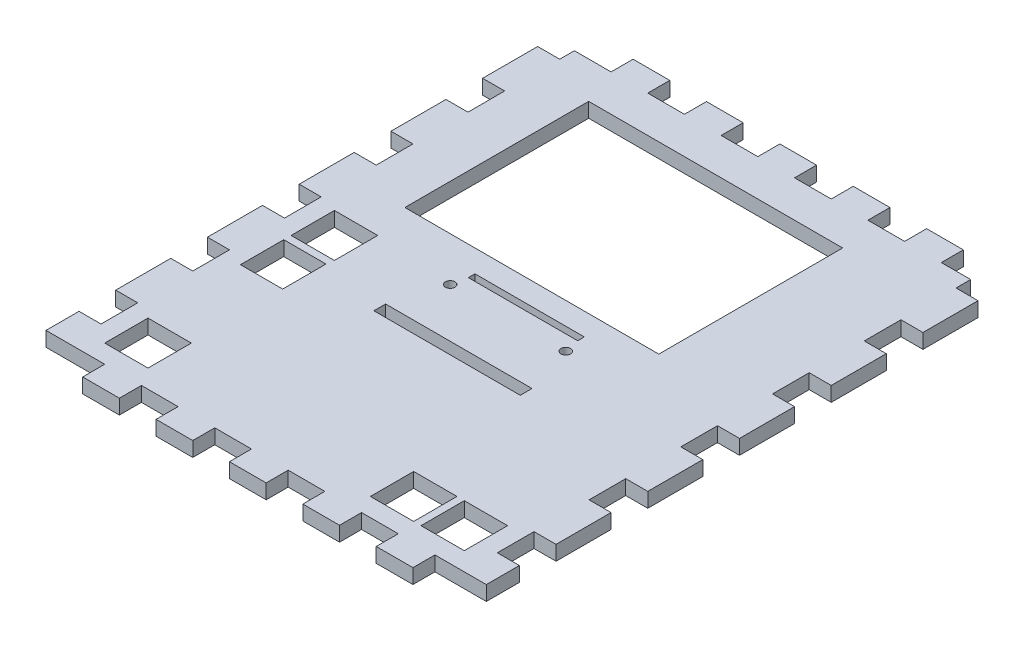
SolidWorks part; units mm, degrees
ref_plane "Спереди" through (0, 0, 0) normal (0, 0, 1) x (1, 0, 0)
ref_plane "Сверху" through (0, 0, 0) normal (0, 1, 0) x (1, 0, 0)
ref_plane "Справа" through (0, 0, 0) normal (1, 0, 0) x (0, 0, -1)
other "Configuration Table"
sketch "Эскиз1" plane through (0, 0, 0) normal (0, 1, 0) x (1, 0, 0)
  line L1 (0, 0) -> (108, 0)
  line L2 (0, 0) -> (0, -138)
  line L3 (0, -138) -> (108, -138)
  line L4 (108, 0) -> (108, -138)
  dimension "D1" = 138
  dimension "D2" = 108
extrude "Бобышка-Вытянуть1" add sketch "Эскиз1" along normal blind 4
sketch "Эскиз2" plane through (0, 4, 0) normal (0, 1, 0) x (1, 0, 0)
  line L0 (0, 0) -> (0, -138) construction
  line L1 (13.9, -10) -> (83.11, -10)
  line L2 (13.9, -10) -> (13.9, -60.1)
  line L3 (13.9, -60.1) -> (83.11, -60.1)
  line L4 (83.11, -10) -> (83.11, -60.1)
  line L6 (108, 0) -> (0, 0) construction
  dimension "D1" = 50.1
  dimension "D2" = 69.21
  dimension "D3" = 13.9
  dimension "D4" = 10
extrude "Вырез-Вытянуть1" cut sketch "Эскиз2" against normal through all
sketch "Эскиз4" plane through (0, 0, 0) normal (-1, 0, 0) x (0, 0, 1)
  line L0 (0, 4) -> (138, 4) construction
  line L1 (4, 4) -> (19, 4)
  line L2 (4, 4) -> (4, 0)
  line L3 (4, 0) -> (19, 0)
  line L4 (19, 4) -> (19, 0)
  line L5 (0, 0) -> (138, 0) construction
  line L6 (0, 4) -> (0, 0) construction
  line L7 (29, 4) -> (29, 0)
  line L8 (29, 4) -> (44, 4)
  line L9 (44, 4) -> (44, 0)
  line L10 (29, 0) -> (44, 0)
  line L11 (54, 4) -> (54, 0)
  line L12 (54, 4) -> (69, 4)
  line L13 (69, 4) -> (69, 0)
  line L14 (54, 0) -> (69, 0)
  line L15 (79, 4) -> (79, 0)
  line L16 (79, 4) -> (94, 4)
  line L17 (94, 4) -> (94, 0)
  line L18 (79, 0) -> (94, 0)
  line L19 (104, 4) -> (104, 0)
  line L20 (104, 4) -> (119, 4)
  line L21 (119, 4) -> (119, 0)
  line L22 (104, 0) -> (119, 0)
  dimension "D1" = 15
  dimension "D2" = 4
  dimension "D3" = 5
extrude "Бобышка-Вытянуть2" add sketch "Эскиз4" along normal blind 6
sketch "Эскиз6" plane through (0, 0, 0) normal (-1, 0, 0) x (0, 0, 1)
  line L0 (119, 0) -> (138, 0) construction
  line L1 (138, 4) -> (129, 4)
  line L2 (138, 4) -> (138, 0)
  line L3 (138, 0) -> (129, 0)
  line L4 (129, 4) -> (129, 0)
  line L5 (119, 0) -> (119, 4) construction
  dimension "D1" = 10
extrude "Бобышка-Вытянуть3" add sketch "Эскиз6" along normal blind 6
sketch "Эскиз7" plane through (108, 0, 0) normal (1, 0, 0) x (0, 0, -1)
  line L0 (-138, 0) -> (0, 0) construction
  line L1 (-4, 4) -> (-19, 4)
  line L2 (-4, 4) -> (-4, 0)
  line L3 (-4, 0) -> (-19, 0)
  line L4 (-19, 4) -> (-19, 0)
  line L5 (-29, 4) -> (-29, 0)
  line L6 (-29, 4) -> (-44, 4)
  line L7 (-44, 4) -> (-44, 0)
  line L8 (-29, 0) -> (-44, 0)
  line L9 (-54, 4) -> (-54, 0)
  line L10 (-54, 4) -> (-69, 4)
  line L11 (-69, 4) -> (-69, 0)
  line L12 (-54, 0) -> (-69, 0)
  line L13 (-79, 4) -> (-79, 0)
  line L14 (-79, 4) -> (-94, 4)
  line L15 (-94, 4) -> (-94, 0)
  line L16 (-79, 0) -> (-94, 0)
  line L17 (-104, 4) -> (-104, 0)
  line L18 (-104, 4) -> (-119, 4)
  line L19 (-119, 4) -> (-119, 0)
  line L20 (-104, 0) -> (-119, 0)
  dimension "D1" = 15
  dimension "D2" = 5
extrude "Бобышка-Вытянуть4" add sketch "Эскиз7" along normal blind 6
sketch "Эскиз8" plane through (108, 0, 0) normal (1, 0, 0) x (0, 0, -1)
  line L0 (-138, 0) -> (-119, 0) construction
  line L1 (-138, 4) -> (-129, 4)
  line L2 (-138, 4) -> (-138, 0)
  line L3 (-138, 0) -> (-129, 0)
  line L4 (-129, 4) -> (-129, 0)
  dimension "D1" = 9
extrude "Бобышка-Вытянуть5" add sketch "Эскиз8" along normal blind 6
sketch "Эскиз9" plane through (0, 0, 0) normal (0, 0, -1) x (-1, 0, 0)
  line L0 (-108, 4) -> (0, 4) construction
  line L1 (-99.9985, 4) -> (-89.9985, 4)
  line L2 (-99.9985, 4) -> (-99.9985, 0)
  line L3 (-99.9985, 0) -> (-89.9985, 0)
  line L4 (-89.9985, 4) -> (-89.9985, 0)
  line L5 (-108, 0) -> (0, 0) construction
  line L6 (-108, 4) -> (-108, 0) construction
  line L7 (-79.9985, 4) -> (-79.9985, 0)
  line L8 (-79.9985, 4) -> (-69.9985, 4)
  line L9 (-69.9985, 4) -> (-69.9985, 0)
  line L10 (-79.9985, 0) -> (-69.9985, 0)
  line L11 (-59.9985, 4) -> (-59.9985, 0)
  line L12 (-59.9985, 4) -> (-49.9985, 4)
  line L13 (-49.9985, 4) -> (-49.9985, 0)
  line L14 (-59.9985, 0) -> (-49.9985, 0)
  line L15 (-39.9985, 4) -> (-39.9985, 0)
  line L16 (-39.9985, 4) -> (-29.9985, 4)
  line L17 (-29.9985, 4) -> (-29.9985, 0)
  line L18 (-39.9985, 0) -> (-29.9985, 0)
  line L19 (-19.9985, 4) -> (-19.9985, 0)
  line L20 (-19.9985, 4) -> (-9.9985, 4)
  line L21 (-9.9985, 4) -> (-9.9985, 0)
  line L22 (-19.9985, 0) -> (-9.9985, 0)
  dimension "D1" = 10
  dimension "D2" = 8.0015
  dimension "D3" = 5
extrude "Бобышка-Вытянуть6" add sketch "Эскиз9" along normal blind 6
sketch "Эскиз10" plane through (0, 0, 138) normal (0, 0, 1) x (1, 0, 0)
  line L0 (-6, 4) -> (114, 4) construction
  line L1 (10, 4) -> (20, 4)
  line L2 (10, 4) -> (10, 0)
  line L3 (10, 0) -> (20, 0)
  line L4 (20, 4) -> (20, 0)
  line L5 (-6, 0) -> (114, 0) construction
  line L6 (-6, 0) -> (-6, 4) construction
  line L7 (30, 4) -> (30, 0)
  line L8 (30, 4) -> (40, 4)
  line L9 (40, 4) -> (40, 0)
  line L10 (30, 0) -> (40, 0)
  line L11 (50, 4) -> (50, 0)
  line L12 (50, 4) -> (60, 4)
  line L13 (60, 4) -> (60, 0)
  line L14 (50, 0) -> (60, 0)
  line L15 (70, 4) -> (70, 0)
  line L16 (70, 4) -> (80, 4)
  line L17 (80, 4) -> (80, 0)
  line L18 (70, 0) -> (80, 0)
  line L19 (90, 4) -> (90, 0)
  line L20 (90, 4) -> (100, 4)
  line L21 (100, 4) -> (100, 0)
  line L22 (90, 0) -> (100, 0)
  point P10 (-6, 2)
  dimension "D1" = 10
  dimension "D2" = 16
  dimension "D3" = 5
extrude "Бобышка-Вытянуть7" add sketch "Эскиз10" along normal blind 6
sketch "Эскиз11" plane through (0, 4, 0) normal (0, 1, 0) x (1, 0, 0)
  line L0 (0, -69) -> (0, -79) construction
  line L1 (5, -84.2) -> (16.5, -84.2)
  line L2 (5, -84.2) -> (5, -96)
  line L3 (5, -96) -> (16.5, -96)
  line L4 (16.5, -84.2) -> (16.5, -96)
  line L5 (5, -70.4) -> (16.8, -70.4)
  line L6 (5, -70.4) -> (5, -82.2)
  line L7 (5, -82.2) -> (16.8, -82.2)
  line L8 (16.8, -70.4) -> (16.8, -82.2)
  line L9 (0, -94) -> (0, -104) construction
  line L10 (-6, -138) -> (10, -138) construction
  dimension "D1" = 11.5
  dimension "D2" = 11.8
  dimension "D3" = 11.8
  dimension "D4" = 11.8
  dimension "D5" = 5
  dimension "D6" = 5
  dimension "D7" = 2
  dimension "D8" = 42
extrude "Вырез-Вытянуть2" cut sketch "Эскиз11" against normal through all
sketch "Эскиз12" plane through (0, 4, 0) normal (0, 1, 0) x (1, 0, 0)
  line L0 (80, -138) -> (90, -138) construction
  line L1 (77.4, -121.2) -> (89.2, -121.2)
  line L2 (77.4, -121.2) -> (77.4, -133)
  line L3 (77.4, -133) -> (89.2, -133)
  line L4 (89.2, -121.2) -> (89.2, -133)
  line L5 (91.2, -121.2) -> (103, -121.2)
  line L6 (91.2, -121.2) -> (91.2, -133)
  line L7 (91.2, -133) -> (103, -133)
  line L8 (103, -121.2) -> (103, -133)
  line L9 (108, -129) -> (108, -119) construction
  dimension "D1" = 11.8
  dimension "D2" = 11.8
  dimension "D3" = 11.8
  dimension "D4" = 11.8
  dimension "D5" = 2
  dimension "D6" = 5
  dimension "D7" = 5
  dimension "D8" = 5
extrude "Вырез-Вытянуть3" cut sketch "Эскиз12" against normal through all
sketch "Эскиз13" plane through (0, 4, 0) normal (0, 1, 0) x (1, 0, 0)
  line L0 (0, -119) -> (0, -129) construction
  line L1 (5, -121.2) -> (16.8, -121.2)
  line L2 (5, -121.2) -> (5, -133)
  line L3 (5, -133) -> (16.8, -133)
  line L4 (16.8, -121.2) -> (16.8, -133)
  line L5 (-6, -138) -> (10, -138) construction
  dimension "D1" = 11.8
  dimension "D2" = 11.8
  dimension "D3" = 5
  dimension "D4" = 5
extrude "Вырез-Вытянуть4" cut sketch "Эскиз13" against normal through all
sketch "Эскиз14" plane through (0, 4, 0) normal (0, 1, 0) x (1, 0, 0)
  line L0 (-6, -67.1) -> (114, -67.1) construction
  line L1 (-6, -69) -> (-6, -54) construction
  line L2 (114, -54) -> (114, -69) construction
  line L3 (13.9, -60.1) -> (83.11, -60.1) construction
  line L4 (-6, -87.1) -> (114, -87.1) construction
  line L5 (39.1, -66.2) -> (68.9, -66.2)
  line L6 (39.1, -66.2) -> (39.1, -68)
  line L7 (39.1, -68) -> (68.9, -68)
  line L8 (68.9, -66.2) -> (68.9, -68)
  line L9 (39.1, -66.2) -> (68.9, -68) construction
  line L10 (39.1, -68) -> (68.9, -66.2) construction
  line L11 (-6, -94) -> (-6, -79) construction
  line L12 (114, -79) -> (114, -94) construction
  line L14 (34.05, -85.5) -> (73.95, -85.5)
  line L15 (34.05, -85.5) -> (34.05, -88.7)
  line L16 (34.05, -88.7) -> (73.95, -88.7)
  line L17 (73.95, -85.5) -> (73.95, -88.7)
  line L18 (34.05, -85.5) -> (73.95, -88.7) construction
  line L19 (34.05, -88.7) -> (73.95, -85.5) construction
  circle A0 centre (38.25, -72.1) radius 1.3
  circle A1 centre (69.75, -72.1) radius 1.3
  point P8 (54, -67.1)
  point P19 (54, -87.1)
  point P28 (36.5528, -73.498)
  point P29 (36.5528, -73.498)
  dimension "D6" = 2.6
  dimension "D7" = 2.6
  dimension "D1" = 7
  dimension "D2" = 29.8
  dimension "D3" = 20
  dimension "D4" = 39.9
  dimension "D5" = 3.2
  dimension "D8" = 31.5
  dimension "D9" = 0.85
  dimension "D10" = 5
  dimension "D11" = 5
extrude "Вырез-Вытянуть5" cut sketch "Эскиз14" against normal through all
